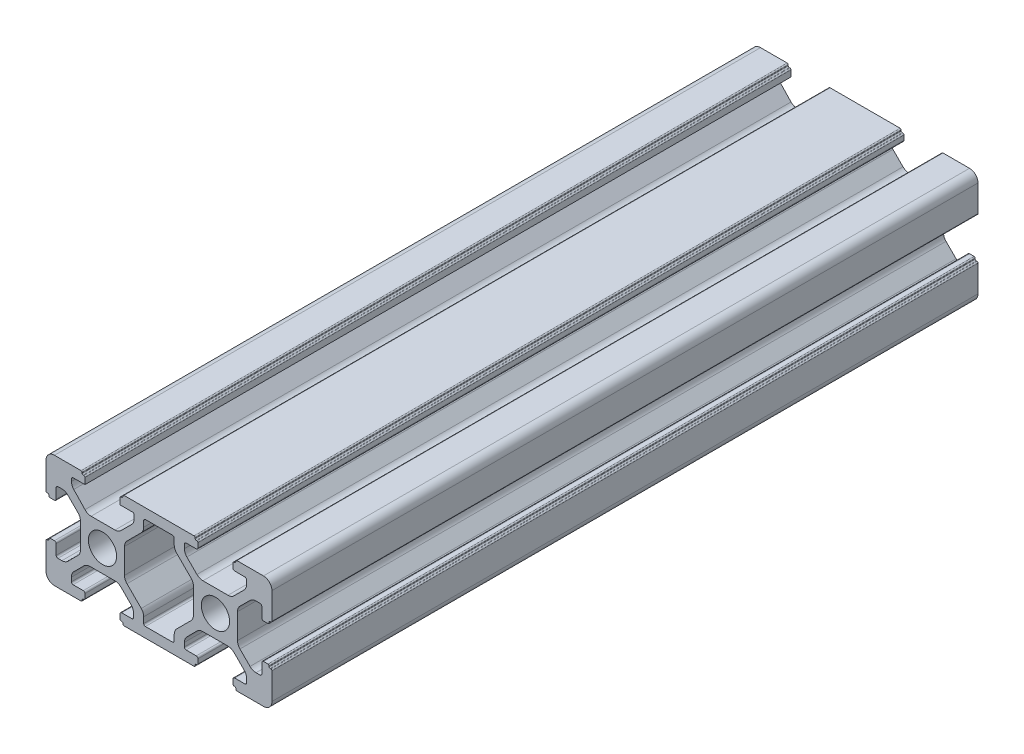
SolidWorks part; units mm, degrees
material "6063-O"
ref_plane "Front Plane" through (0, 0, 0) normal (0, 0, 1) x (1, 0, 0)
ref_plane "Top Plane" through (0, 0, 0) normal (0, 1, 0) x (1, 0, 0)
ref_plane "Right Plane" through (0, 0, 0) normal (1, 0, 0) x (0, 0, -1)
sketch "Sketch1" plane through (0, 0, 0) normal (0, 0, 1) x (1, 0, 0)
  line L0 (1.5, 0) -> (6.2, 0)
  line L1 (40, 1.5) -> (40, 6.2)
  line L2 (38.5, 20) -> (33.8, 20)
  line L3 (0, 18.5) -> (0, 13.8)
  line L4 (17.6, 1.8) -> (22.4, 1.8)
  line L5 (32.218, 13.9) -> (27.782, 13.9)
  line L6 (26.1, 12.218) -> (26.1, 7.782)
  line L7 (17.6, 18.2) -> (22.4, 18.2)
  line L8 (12.218, 13.9) -> (7.9864, 13.9)
  line L9 (6.1, 12.218) -> (6.1, 7.782)
  line L10 (7.782, 6.1) -> (12.218, 6.1)
  line L11 (13.9, 7.782) -> (13.9, 12.218)
  line L12 (27.782, 6.1) -> (32.218, 6.1)
  line L13 (33.9, 7.782) -> (33.9, 12.218)
  line L14 (26.7213, 14.3393) -> (24.9393, 16.1213)
  line L15 (33.2787, 14.3393) -> (35.0607, 16.1213)
  line L16 (34.3393, 13.2787) -> (36.1213, 15.0607)
  line L17 (25.6607, 6.7213) -> (23.1393, 4.2)
  line L18 (15.2, 1.8) -> (13.4, 1.8)
  line L19 (26.7213, 5.6607) -> (24.9393, 3.8787)
  line L20 (24.8, 1.8) -> (26.6, 1.8)
  line L21 (15.3, 18.2) -> (13.1, 18.2)
  line L22 (13.2787, 14.3393) -> (15.1607, 16.2213)
  line L23 (14.3393, 13.2787) -> (16.8607, 15.8)
  line L24 (5.6607, 6.7213) -> (3.8787, 4.9393)
  line L25 (6.7213, 5.6607) -> (4.9393, 3.8787)
  line L26 (6.897, 14.3689) -> (4.9106, 16.4674)
  line L27 (5.6607, 13.2787) -> (3.8787, 15.0607)
  line L28 (14.3393, 6.7213) -> (16.8607, 4.2)
  line L29 (13.2787, 5.6607) -> (15.0607, 3.8787)
  line L30 (24.8, 18.2) -> (26.6, 18.2)
  line L31 (25.6607, 13.2787) -> (23.1393, 15.8)
  line L32 (34.3393, 6.7213) -> (36.1213, 4.9393)
  line L33 (33.2787, 5.6607) -> (35.0607, 3.8787)
  line L34 (1.8, 15.2) -> (1.8, 13.4)
  line L35 (24.5, 2.1) -> (24.5, 2.818)
  line L36 (4.5, 2.1) -> (4.5, 2.818)
  line L37 (2.818, 4.5) -> (2.1, 4.5)
  line L38 (4.5, 17.9) -> (4.5, 17.4986)
  line L39 (2.818, 15.5) -> (2.1, 15.5)
  line L40 (15.6, 17.9) -> (15.6, 17.282)
  line L41 (15.5, 2.818) -> (15.5, 2.1)
  line L42 (38.2, 15.2) -> (38.2, 13.4)
  line L43 (35.5, 2.818) -> (35.5, 2.1)
  line L44 (37.182, 4.5) -> (37.9, 4.5)
  line L45 (35.5, 17.182) -> (35.5, 17.9)
  line L46 (37.182, 15.5) -> (37.9, 15.5)
  line L47 (17.3, 2.1) -> (17.3, 3.1393)
  line L48 (22.7, 2.1) -> (22.7, 3.1393)
  line L49 (17.3, 17.9) -> (17.3, 16.8607)
  line L50 (22.7, 17.9) -> (22.7, 16.8607)
  line L51 (24.5, 17.9) -> (24.5, 17.182)
  line L52 (6.9, 19.3) -> (6.9, 18.2)
  line L53 (13.1, 19.3) -> (13.1, 18.2)
  line L54 (6.9, 1.5) -> (6.9, 0.7)
  line L55 (13.1, 1.5) -> (13.1, 0.7)
  line L56 (13.8, 0) -> (26.2, 0)
  line L57 (6.6, 1.8) -> (4.8, 1.8)
  line L58 (6.9, 18.2) -> (4.8, 18.2)
  line L59 (6.2, 20) -> (1.5, 20)
  line L60 (39.3, 6.9) -> (38.5, 6.9)
  line L61 (39.3, 13.1) -> (38.5, 13.1)
  line L62 (1.5, 13.1) -> (0.7, 13.1)
  line L63 (1.5, 6.9) -> (0.7, 6.9)
  line L64 (0, 6.2) -> (0, 1.5)
  line L65 (1.8, 6.6) -> (1.8, 4.8)
  line L66 (38.2, 6.6) -> (38.2, 4.8)
  line L67 (40, 13.8) -> (40, 18.5)
  line L68 (33.1, 19.3) -> (33.1, 18.5)
  line L69 (26.9, 19.3) -> (26.9, 18.5)
  line L70 (26.9, 1.5) -> (26.9, 0.7)
  line L71 (33.1, 1.5) -> (33.1, 0.7)
  line L72 (33.8, 0) -> (38.5, 0)
  line L73 (33.4, 1.8) -> (35.2, 1.8)
  line L74 (26.2, 20) -> (13.8, 20)
  line L75 (33.4, 18.2) -> (35.2, 18.2)
  line L76 (6.7, 0.5) -> (6.6, 0.5)
  line L77 (6.4, 0.3) -> (6.4, 0.2)
  line L78 (13.3, 0.5) -> (13.4, 0.5)
  line L79 (13.6, 0.3) -> (13.6, 0.2)
  line L80 (26.7, 0.5) -> (26.6, 0.5)
  line L81 (26.4, 0.3) -> (26.4, 0.2)
  line L82 (33.3, 0.5) -> (33.4, 0.5)
  line L83 (33.6, 0.3) -> (33.6, 0.2)
  line L85 (6.4, 19.8) -> (6.4, 19.7)
  line L86 (6.6, 19.5) -> (6.7, 19.5)
  line L87 (13.6, 19.8) -> (13.6, 19.7)
  line L88 (13.4, 19.5) -> (13.3, 19.5)
  line L89 (26.4, 19.8) -> (26.4, 19.7)
  line L90 (26.6, 19.5) -> (26.7, 19.5)
  line L91 (33.6, 19.8) -> (33.6, 19.7)
  line L92 (33.4, 19.5) -> (33.3, 19.5)
  line L93 (0.5, 13.3) -> (0.5, 13.4)
  line L94 (0.3, 13.6) -> (0.2, 13.6)
  line L95 (0.5, 6.7) -> (0.5, 6.6)
  line L96 (0.3, 6.4) -> (0.2, 6.4)
  line L97 (39.5, 13.3) -> (39.5, 13.4)
  line L98 (39.7, 13.6) -> (39.8, 13.6)
  line L99 (39.5, 6.7) -> (39.5, 6.6)
  line L100 (39.7, 6.4) -> (39.8, 6.4)
  circle A0 centre (10, 10) radius 2.5
  circle A1 centre (30, 10) radius 2.5
  arc A2 (38.5, 0) -> (40, 1.5) centre (38.5, 1.5) ccw
  arc A3 (40, 18.5) -> (38.5, 20) centre (38.5, 18.5) ccw
  arc A4 (1.5, 0) -> (0, 1.5) centre (1.5, 1.5) cw
  arc A5 (1.5, 20) -> (0, 18.5) centre (1.5, 18.5) ccw
  arc A6 (26.7213, 5.6607) -> (27.782, 6.1) centre (27.782, 4.6) cw
  arc A7 (32.218, 6.1) -> (33.2787, 5.6607) centre (32.218, 4.6) cw
  arc A8 (33.9, 7.782) -> (34.3393, 6.7213) centre (35.4, 7.782) ccw
  arc A9 (33.2787, 14.3393) -> (32.218, 13.9) centre (32.218, 15.4) cw
  arc A10 (14.3393, 6.7213) -> (13.9, 7.782) centre (15.4, 7.782) cw
  arc A11 (14.3393, 13.2787) -> (13.9, 12.218) centre (15.4, 12.218) ccw
  arc A12 (25.6607, 6.7213) -> (26.1, 7.782) centre (24.6, 7.782) ccw
  arc A13 (26.1, 12.218) -> (25.6607, 13.2787) centre (24.6, 12.218) ccw
  arc A14 (27.782, 13.9) -> (26.7213, 14.3393) centre (27.782, 15.4) cw
  arc A15 (5.6607, 13.2787) -> (6.1, 12.218) centre (4.6, 12.218) cw
  arc A16 (5.6607, 6.7213) -> (6.1, 7.782) centre (4.6, 7.782) ccw
  arc A17 (13.2787, 5.6607) -> (12.218, 6.1) centre (12.218, 4.6) ccw
  arc A18 (6.7213, 5.6607) -> (7.782, 6.1) centre (7.782, 4.6) cw
  arc A19 (13.2787, 14.3393) -> (12.218, 13.9) centre (12.218, 15.4) cw
  arc A20 (6.897, 14.3689) -> (7.9864, 13.9) centre (7.9864, 15.4) ccw
  arc A21 (36.1213, 4.9393) -> (37.182, 4.5) centre (37.182, 6) ccw
  arc A22 (36.1213, 15.0607) -> (37.182, 15.5) centre (37.182, 14) cw
  arc A23 (35.0607, 16.1213) -> (35.5, 17.182) centre (34, 17.182) ccw
  arc A24 (24.5, 17.182) -> (24.9393, 16.1213) centre (26, 17.182) ccw
  arc A25 (22.7, 16.8607) -> (23.1393, 15.8) centre (24.2, 16.8607) ccw
  arc A26 (17.3, 16.8607) -> (16.8607, 15.8) centre (15.8, 16.8607) cw
  arc A27 (4.9106, 16.4674) -> (4.5, 17.4986) centre (6, 17.4986) cw
  arc A28 (15.6, 17.282) -> (15.1607, 16.2213) centre (14.1, 17.282) cw
  arc A29 (3.8787, 15.0607) -> (2.818, 15.5) centre (2.818, 14) ccw
  arc A30 (3.8787, 4.9393) -> (2.818, 4.5) centre (2.818, 6) cw
  arc A31 (4.9393, 3.8787) -> (4.5, 2.818) centre (6, 2.818) ccw
  arc A32 (35.0607, 3.8787) -> (35.5, 2.818) centre (34, 2.818) cw
  arc A33 (24.9393, 3.8787) -> (24.5, 2.818) centre (26, 2.818) ccw
  arc A34 (22.7, 3.1393) -> (23.1393, 4.2) centre (24.2, 3.1393) cw
  arc A35 (17.3, 3.1393) -> (16.8607, 4.2) centre (15.8, 3.1393) ccw
  arc A36 (15.5, 2.818) -> (15.0607, 3.8787) centre (14, 2.818) ccw
  arc A37 (1.8, 6.6) -> (1.5, 6.9) centre (1.5, 6.6) ccw
  arc A38 (1.8, 13.4) -> (1.5, 13.1) centre (1.5, 13.4) cw
  arc A39 (17.6, 18.2) -> (17.3, 17.9) centre (17.6, 17.9) ccw
  arc A40 (22.4, 1.8) -> (22.7, 2.1) centre (22.4, 2.1) ccw
  arc A41 (17.6, 1.8) -> (17.3, 2.1) centre (17.6, 2.1) cw
  arc A42 (15.2, 1.8) -> (15.5, 2.1) centre (15.2, 2.1) ccw
  arc A43 (6.6, 1.8) -> (6.9, 1.5) centre (6.6, 1.5) cw
  arc A44 (13.4, 1.8) -> (13.1, 1.5) centre (13.4, 1.5) ccw
  arc A45 (24.8, 1.8) -> (24.5, 2.1) centre (24.8, 2.1) cw
  arc A46 (35.2, 1.8) -> (35.5, 2.1) centre (35.2, 2.1) ccw
  arc A47 (26.6, 1.8) -> (26.9, 1.5) centre (26.6, 1.5) cw
  arc A48 (33.4, 1.8) -> (33.1, 1.5) centre (33.4, 1.5) ccw
  arc A49 (26.9, 18.5) -> (26.6, 18.2) centre (26.6, 18.5) cw
  arc A50 (33.1, 18.5) -> (33.4, 18.2) centre (33.4, 18.5) ccw
  arc A51 (37.9, 4.5) -> (38.2, 4.8) centre (37.9, 4.8) ccw
  arc A52 (38.5, 13.1) -> (38.2, 13.4) centre (38.5, 13.4) cw
  arc A53 (38.5, 6.9) -> (38.2, 6.6) centre (38.5, 6.6) ccw
  arc A54 (38.2, 15.2) -> (37.9, 15.5) centre (37.9, 15.2) ccw
  arc A55 (35.2, 18.2) -> (35.5, 17.9) centre (35.2, 17.9) cw
  arc A56 (24.8, 18.2) -> (24.5, 17.9) centre (24.8, 17.9) ccw
  arc A57 (22.4, 18.2) -> (22.7, 17.9) centre (22.4, 17.9) cw
  arc A58 (15.3, 18.2) -> (15.6, 17.9) centre (15.3, 17.9) cw
  arc A59 (4.5, 17.9) -> (4.8, 18.2) centre (4.8, 17.9) cw
  arc A60 (1.8, 15.2) -> (2.1, 15.5) centre (2.1, 15.2) cw
  arc A61 (1.8, 4.8) -> (2.1, 4.5) centre (2.1, 4.8) ccw
  arc A62 (4.5, 2.1) -> (4.8, 1.8) centre (4.8, 2.1) ccw
  arc A63 (34.3393, 13.2787) -> (33.9, 12.218) centre (35.4, 12.218) ccw
  arc A64 (6.4, 0.2) -> (6.2, 0) centre (6.2, 0.2) cw
  arc A65 (6.6, 0.5) -> (6.4, 0.3) centre (6.6, 0.3) ccw
  arc A66 (6.7, 0.5) -> (6.9, 0.7) centre (6.7, 0.7) ccw
  arc A67 (13.6, 0.2) -> (13.8, 0) centre (13.8, 0.2) ccw
  arc A68 (13.4, 0.5) -> (13.6, 0.3) centre (13.4, 0.3) cw
  arc A69 (13.3, 0.5) -> (13.1, 0.7) centre (13.3, 0.7) cw
  arc A70 (26.4, 0.2) -> (26.2, 0) centre (26.2, 0.2) cw
  arc A71 (26.6, 0.5) -> (26.4, 0.3) centre (26.6, 0.3) ccw
  arc A72 (26.7, 0.5) -> (26.9, 0.7) centre (26.7, 0.7) ccw
  arc A73 (33.6, 0.2) -> (33.8, 0) centre (33.8, 0.2) ccw
  arc A74 (33.4, 0.5) -> (33.6, 0.3) centre (33.4, 0.3) cw
  arc A75 (33.3, 0.5) -> (33.1, 0.7) centre (33.3, 0.7) cw
  arc A76 (39.8, 6.4) -> (40, 6.2) centre (39.8, 6.2) cw
  arc A77 (39.5, 6.6) -> (39.7, 6.4) centre (39.7, 6.6) ccw
  arc A78 (39.5, 6.7) -> (39.3, 6.9) centre (39.3, 6.7) ccw
  arc A79 (39.5, 13.3) -> (39.3, 13.1) centre (39.3, 13.3) cw
  arc A80 (39.5, 13.4) -> (39.7, 13.6) centre (39.7, 13.4) cw
  arc A81 (39.8, 13.6) -> (40, 13.8) centre (39.8, 13.8) ccw
  arc A82 (33.3, 19.5) -> (33.1, 19.3) centre (33.3, 19.3) ccw
  arc A83 (33.6, 19.7) -> (33.4, 19.5) centre (33.4, 19.7) cw
  arc A84 (33.6, 19.8) -> (33.8, 20) centre (33.8, 19.8) cw
  arc A85 (26.7, 19.5) -> (26.9, 19.3) centre (26.7, 19.3) cw
  arc A86 (26.4, 19.7) -> (26.6, 19.5) centre (26.6, 19.7) ccw
  arc A87 (26.4, 19.8) -> (26.2, 20) centre (26.2, 19.8) ccw
  arc A88 (0.2, 6.4) -> (0, 6.2) centre (0.2, 6.2) ccw
  arc A89 (0.5, 6.6) -> (0.3, 6.4) centre (0.3, 6.6) cw
  arc A90 (0.5, 6.7) -> (0.7, 6.9) centre (0.7, 6.7) cw
  arc A91 (13.3, 19.5) -> (13.1, 19.3) centre (13.3, 19.3) ccw
  arc A92 (13.6, 19.7) -> (13.4, 19.5) centre (13.4, 19.7) cw
  arc A93 (13.6, 19.8) -> (13.8, 20) centre (13.8, 19.8) cw
  arc A94 (6.2, 20) -> (6.4, 19.8) centre (6.2, 19.8) cw
  arc A95 (6.7, 19.5) -> (6.9, 19.3) centre (6.7, 19.3) cw
  arc A96 (6.4, 19.7) -> (6.6, 19.5) centre (6.6, 19.7) ccw
  arc A97 (0.5, 13.3) -> (0.7, 13.1) centre (0.7, 13.3) ccw
  arc A98 (0.2, 13.6) -> (0, 13.8) centre (0.2, 13.8) cw
  arc A99 (0.5, 13.4) -> (0.3, 13.6) centre (0.3, 13.4) ccw
  point P87 (0, 0)
  point P178 (1.8, 6.9)
  point P181 (1.8, 13.1)
  point P186 (22.7, 1.8)
  point P193 (6.9, 1.8)
  point P204 (33.1, 1.8)
  point P209 (33.1, 18.2)
  point P216 (38.2, 6.9)
  point P243 (6.9, 0.5)
  point P248 (13.6, 0.5)
  point P257 (26.9, 0.5)
extrude "Boss-Extrude2" add sketch "Sketch1" along normal blind 125 contours A57 L7 A39 L49 A26 L23 A11 L11 A10 L28 A35 L47 A41 L4 A40 L48 A34 L17 A12 L6 A13 L31 A25 L50 | A0 | A1 | L59 A5 L3 A98 L94 A99 L93 A97 L62 A38 L34 A60 L39 A29 L27 A15 L9 A16 L24 A30 L37 A61 L65 A37 L63 A90 L95 A89 L96 A88 L64 A4 L0 A64 L77 A65 L76 A66 L54 A43 L57 A62 L36 A31 L25 A18 L10 A17 L29 A36 L41 A42 L18 A44 L55 A69 L78 A68 L79 A67 L56 A70 L81 A71 L80 A72 L70 A47 L20 A45 L35 A33 L19 A6 L12 A7 L33 A32 L43 A46 L73 A48 L71 A75 L82 A74 L83 A73 L72 A2 L1 A76 L100 A77 L99 A78 L60 A53 L66 A51 L44 A21 L32 A8 L13 A63 L16 A22 L46 A54 L42 A52 L61 A79 L97 A80 L98 A81 L67 A3 L2 A84 L91 A83 L92 A82 L68 A50 L75 A55 L45 A23 L15 A9 L5 A14 L14 A24 L51 A56 L30 A49 L69 A85 L90 A86 L89 A87 L74 A93 L87 A92 L88 A91 L53 L21 A58 L40 A28 L22 A19 L8 A20 L26 A27 L38 A59 L58 L52 A95 L86 A96 L85 A94
